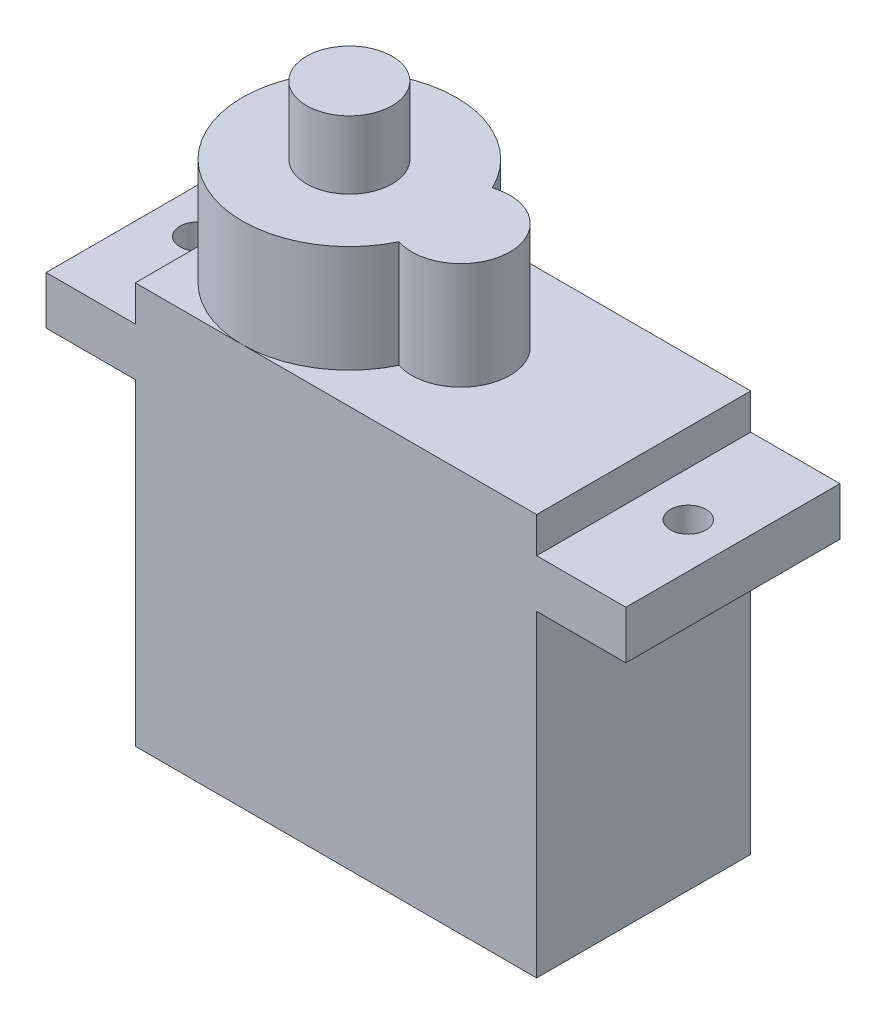
SolidWorks part; units mm, degrees
ref_plane "前视基准面" through (0, 0, 0) normal (0, 0, 1) x (1, 0, 0)
ref_plane "上视基准面" through (0, 0, 0) normal (0, 1, 0) x (1, 0, 0)
ref_plane "右视基准面" through (0, 0, 0) normal (1, 0, 0) x (0, 0, -1)
sketch "草图1" plane through (0, 0, 0) normal (0, 0, 1) x (1, 0, 0)
  line L1 (11.25, -11.25) -> (-11.25, -11.25)
  line L2 (11.25, -11.25) -> (11.25, 11.25)
  line L3 (11.25, 11.25) -> (-11.25, 11.25)
  line L4 (-11.25, -11.25) -> (-11.25, 11.25)
  line L5 (11.25, -11.25) -> (-11.25, 11.25) construction
  line L6 (11.25, 11.25) -> (-11.25, -11.25) construction
  point P0 (0, 0)
  dimension "D1" = 22.5
  dimension "D2" = 22.5
extrude "凸台-拉伸1" add sketch "草图1" against normal blind 12
sketch "草图2" plane through (11.25, 0, 0) normal (1, 0, 0) x (0, 0, -1)
  line L0 (0, -11.25) -> (0, 11.25) construction
  line L1 (0, 9.25) -> (12, 9.25)
  line L2 (0, 9.25) -> (0, 6.55)
  line L3 (0, 6.55) -> (12, 6.55)
  line L4 (12, 9.25) -> (12, 6.55)
  line L5 (12, -11.25) -> (12, 11.25) construction
  line L6 (12, 11.25) -> (0, 11.25) construction
  dimension "D1" = 2
  dimension "D2" = 2.7
extrude "凸台-拉伸2" add sketch "草图2" along normal blind 5
sketch "草图4" plane through (0, 9.25, 0) normal (0, 1, 0) x (1, 0, 0)
  line L0 (-11.25, 6) -> (22.6649, 6) construction
  line L1 (-11.25, 12) -> (-11.25, 0) construction
  line L2 (16.25, 12) -> (16.25, 0) construction
  circle A0 centre (13.75, 6) radius 1
  dimension "D1" = 2
  dimension "D2" = 2.5
extrude "切除-拉伸1" cut sketch "草图4" against normal up to next and the other way through all
mirror "镜向1" about plane through (0, 0, 0) normal (1, 0, 0) of bodies 108
sketch "草图5" plane through (0, 11.25, 0) normal (0, 1, 0) x (1, 0, 0)
  line L0 (-11.25, 12) -> (-11.25, 0) construction
  line L2 (11.25, 12) -> (-11.25, 12) construction
  line L3 (11.25, 0) -> (-11.25, 0) construction
  line L4 (-23.0603, 6) -> (-1.75, 6) construction
  line L5 (11.25, 12) -> (11.25, 0) construction
  line L6 (0.75, 6) -> (23.8647, 6) construction
  arc A0 (0.15, 8.6153) -> (0.15, 3.3847) centre (-5.25, 6) ccw
  arc A1 (0.15, 3.3847) -> (0.15, 8.6153) centre (1, 6) ccw
  dimension "D1" = 7.5
  dimension "D2" = 5.5
extrude "凸台-拉伸3" add sketch "草图5" along normal blind 6 contours A0 A1
sketch "草图6" plane through (0, 17.25, 0) normal (0, 1, 0) x (1, 0, 0)
  circle A0 centre (-5.25, 6) radius 2.4
  arc A1 (-5.25, 12) -> (-11.25, 6) centre (-5.25, 6) ccw construction
  dimension "D1" = 4.8
extrude "凸台-拉伸4" add sketch "草图6" along normal blind 3.8
